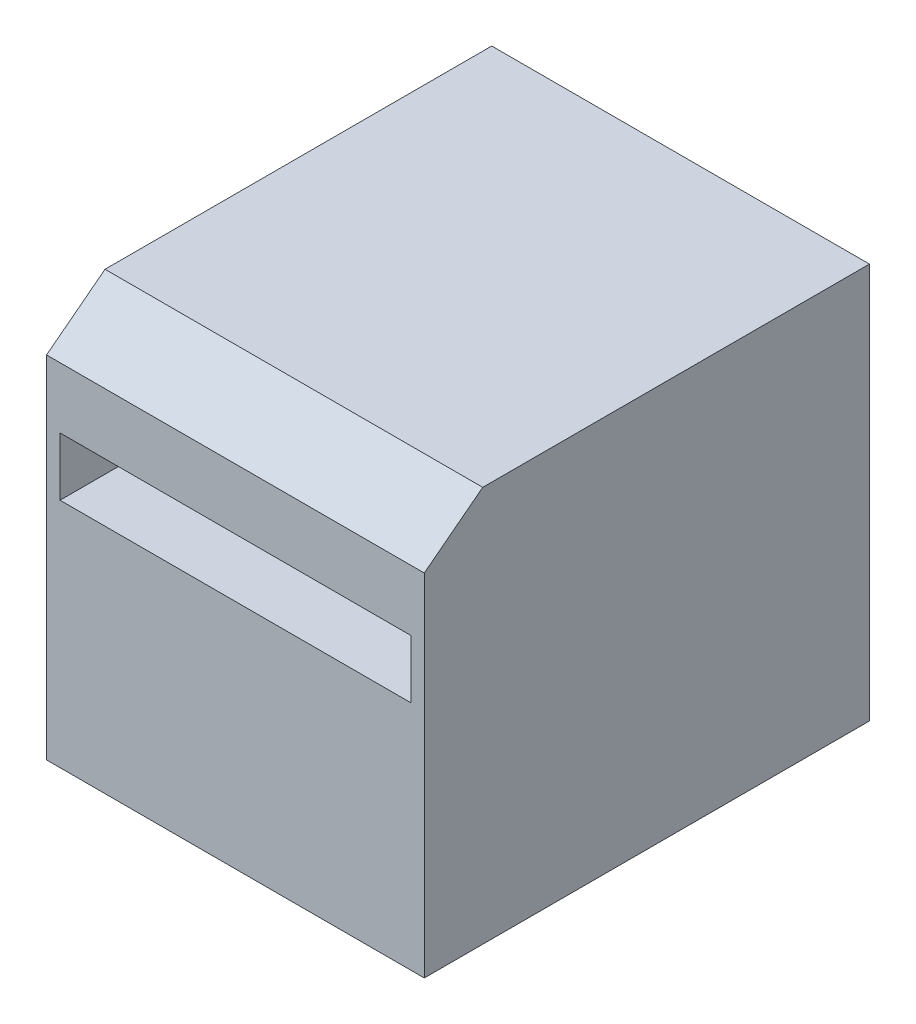
SolidWorks part; units mm, degrees
ref_plane "Front Plane" through (0, 0, 0) normal (0, 0, 1) x (1, 0, 0)
ref_plane "Top Plane" through (0, 0, 0) normal (0, 1, 0) x (1, 0, 0)
ref_plane "Right Plane" through (0, 0, 0) normal (1, 0, 0) x (0, 0, -1)
sketch "Sketch1" plane through (0, 0, 0) normal (1, 0, 0) x (0, 0, -1)
  line L0 (0, 0) -> (0, 78)
  line L1 (0, 0) -> (99, 0)
  line L2 (99, 0) -> (99, 88)
  line L3 (99, 88) -> (13, 88)
  line L4 (0, 78) -> (13, 88)
  dimension "D1" = 78
  dimension "D2" = 99
  dimension "D3" = 88
  dimension "D4" = 86
extrude "Boss-Extrude1" add sketch "Sketch1" along normal blind 84
sketch "Sketch2" plane through (0, 0, -99) normal (0, 0, -1) x (-1, 0, 0)
  line L0 (-42, 88) -> (-42, 63) construction
  line L1 (-84, 88) -> (0, 88) construction
  line L2 (-42, 63) -> (-42, 58) construction
  line L4 (-3, 51.5189) -> (-81, 51.5189)
  line L5 (-3, 51.5189) -> (-3, 64.4811)
  line L6 (-3, 64.4811) -> (-81, 64.4811)
  line L7 (-81, 51.5189) -> (-81, 64.4811)
  line L8 (-42, 64.4811) -> (-42, 51.5189) construction
  line L9 (-3, 58) -> (-81, 58) construction
  dimension "D1" = 25
  dimension "D2" = 5
  dimension "D3" = 78
extrude "Cut-Extrude1" cut sketch "Sketch2" against normal through all
